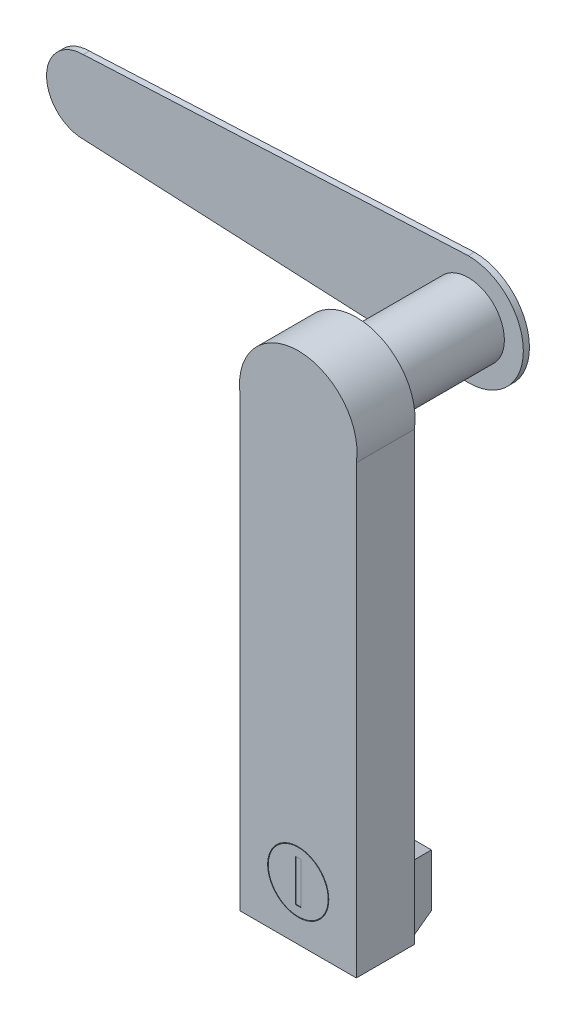
SolidWorks part; units mm, degrees
material "鑄合金鋼"
ref_plane "前基準面" through (0, 0, 0) normal (0, 0, 1) x (1, 0, 0)
ref_plane "上基準面" through (0, 0, 0) normal (0, 1, 0) x (1, 0, 0)
ref_plane "右基準面" through (0, 0, 0) normal (1, 0, 0) x (0, 0, -1)
sketch "草圖1" plane through (0, 0, 0) normal (0, 0, 1) x (1, 0, 0)
  line L0 (0, 61.7749) -> (0, -62.7108) construction
  line L1 (-72.3827, 0) -> (66.7668, 0) construction
  line L4 (-9.5, 36) -> (-9.5, -37)
  line L5 (-9.5, -37) -> (9.5, -37)
  line L6 (9.5, 36) -> (9.5, -37)
  arc A0 (9.5, 36) -> (-9.5, 36) centre (0, 37.5) ccw
  dimension "D1" = 19
  dimension "D2" = 37
extrude "伸長1" add sketch "草圖1" against normal blind 9.5
sketch "草圖2" plane through (0, 0, -9.5) normal (0, 0, -1) x (-1, 0, 0)
  line L6 (-9, -25.5) -> (9, -25.5)
  line L7 (9, -36.5) -> (9, -25.5)
  line L8 (-9, -36.5) -> (9, -36.5)
  line L9 (-9, -36.5) -> (-9, -25.5)
extrude "伸長2" add sketch "草圖2" along normal blind 4.5 draft 15
sketch "草圖3" plane through (0, 0, 0) normal (0, 0, 1) x (1, 0, 0)
  line L0 (0, -37) -> (0, 47.1177) construction
  line L1 (-9.5, -37) -> (9.5, -37) construction
  arc A0 (9.5, 36) -> (-9.5, 36) centre (0, 37.5) ccw construction
  circle A1 centre (0, -28.1506) radius 5
extrude "除料-伸長1" cut sketch "草圖3" against normal blind 5
sketch "草圖4" plane through (0, 0, -5) normal (0, 0, 1) x (1, 0, 0)
  circle A0 centre (0, -28.1506) radius 4.9
extrude "伸長3" add sketch "草圖4" along normal blind 5
sketch "草圖5" plane through (0, 0, 0) normal (0, 0, 1) x (1, 0, 0)
  line L0 (0, -33.0506) -> (0, -23.2506) construction
  line L2 (5, -28.1506) -> (-5, -28.1506) construction
  line L4 (-0.4891, -24.731) -> (0.4891, -24.731)
  line L5 (-0.4891, -24.731) -> (-0.4891, -31.5701)
  line L6 (-0.4891, -31.5701) -> (0.4891, -31.5701)
  line L7 (0.4891, -24.731) -> (0.4891, -31.5701)
  circle A0 centre (0, -28.1506) radius 5 construction
  circle A1 centre (0, -28.1506) radius 5 construction
  circle A2 centre (0, -28.1506) radius 4.9 construction
  circle A3 centre (0, -28.1506) radius 4.9 construction
extrude "除料-伸長2" cut sketch "草圖5" against normal blind 0.1
sketch "草圖7" plane through (0, 0, -9.5) normal (0, 0, -1) x (-1, 0, 0)
  circle A0 centre (0.1756, 37.4978) radius 5.9
extrude "伸長4" add sketch "草圖7" along normal blind 18.5
sketch "草圖8" plane through (0, 0, -28) normal (0, 0, -1) x (-1, 0, 0)
  line L0 (0.1756, 46.4978) -> (0.1756, 28.4978) construction
  line L1 (63.1756, 55.2052) -> (63.1756, 25.2674) construction
  line L2 (0.1756, 37.4978) -> (63.1756, 37.4978) construction
  line L3 (0.1756, 46.4978) -> (63.1756, 43.4978)
  line L4 (63.1756, 31.4978) -> (0.1756, 28.4978)
  arc A0 (0.1756, 46.4978) -> (0.1756, 28.4978) centre (0.1756, 37.4978) ccw
  arc A1 (63.1756, 31.4978) -> (63.1756, 43.4978) centre (63.1756, 37.4978) ccw
  dimension "D1" = 63
extrude "伸長5" add sketch "草圖8" along normal blind 1
